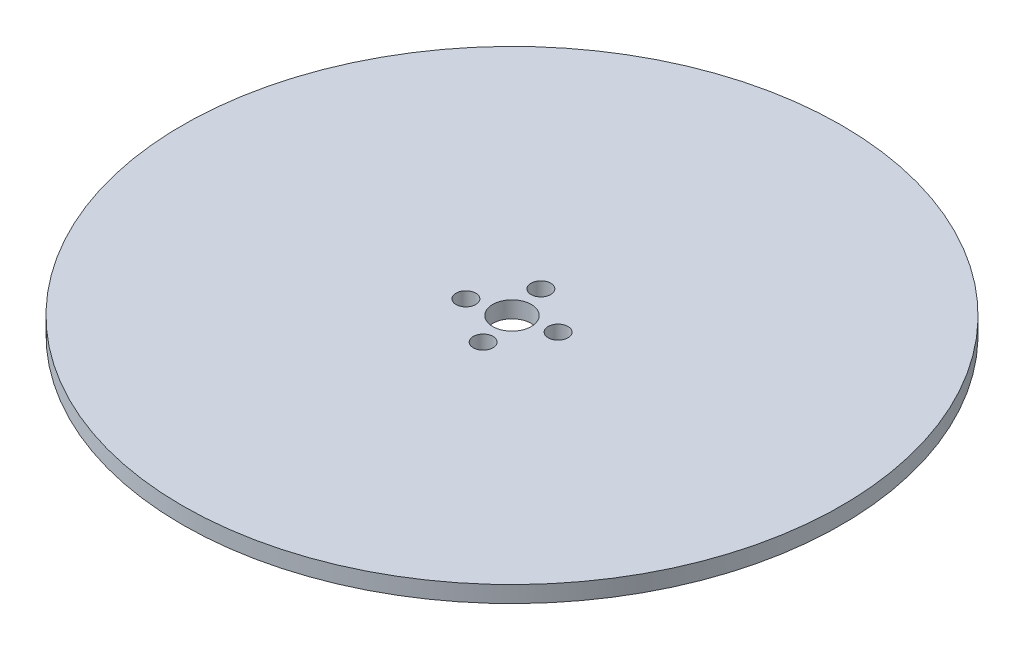
SolidWorks part; units mm, degrees
ref_plane "Front Plane" through (0, 0, 0) normal (0, 0, 1) x (1, 0, 0)
ref_plane "Top Plane" through (0, 0, 0) normal (0, 1, 0) x (1, 0, 0)
ref_plane "Right Plane" through (0, 0, 0) normal (1, 0, 0) x (0, 0, -1)
sketch "Sketch1" plane through (0, 0, 0) normal (0, 1, 0) x (1, 0, 0)
  circle A0 centre (0, 0) radius 60
  dimension "D1" = 120
extrude "Boss-Extrude1" add sketch "Sketch1" along normal blind 3
sketch "Sketch2" plane through (0, 0, 0) normal (0, -1, 0) x (1, 0, 0)
  circle A0 centre (0, 0) radius 3.5
  circle A1 centre (6.8217, -1.5699) radius 1.8
  circle A2 centre (-1.5699, -6.8217) radius 1.8
  circle A3 centre (-6.8217, 1.5699) radius 1.8
  circle A4 centre (1.5699, 6.8217) radius 1.8
  dimension "D1" = 3.6
  dimension "D2" = 7
extrude "Cut-Extrude1" cut sketch "Sketch2" against normal up to next contours A0 | A4 | A1 | A2 | A3
sketch "Sketch3" plane through (0, 0, 0) normal (0, -1, 0) x (1, 0, 0)
  circle A0 centre (0, 0) radius 54
  circle A1 centre (0, 0) radius 36
  dimension "D1" = 108
  dimension "D2" = 72
extrude "Boss-Extrude2" add sketch "Sketch3" along normal blind 3 contours A0 A1
